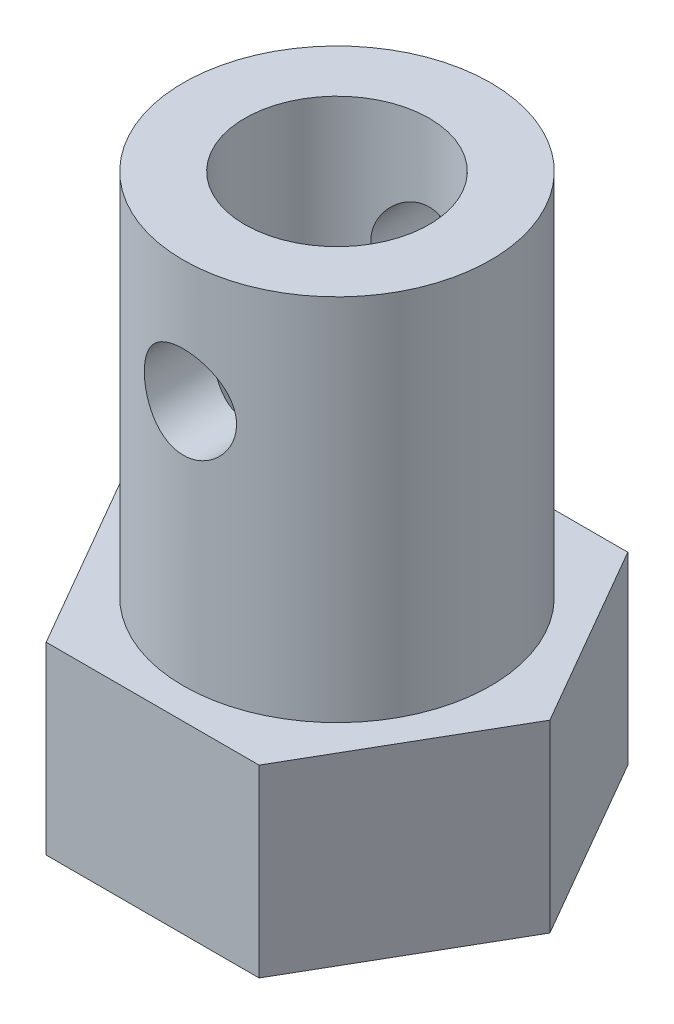
SolidWorks part; units mm, degrees
material "Brass"
ref_plane "Front Plane" through (0, 0, 0) normal (0, 0, 1) x (1, 0, 0)
ref_plane "Top Plane" through (0, 0, 0) normal (0, 1, 0) x (1, 0, 0)
ref_plane "Right Plane" through (0, 0, 0) normal (1, 0, 0) x (0, 0, -1)
sketch "Sketch1" plane through (0, 0, 0) normal (0, 1, 0) x (1, 0, 0)
  line L1 (6.9282, 0) -> (3.4641, 6)
  line L2 (3.4641, 6) -> (-3.4641, 6)
  line L3 (-3.4641, 6) -> (-6.9282, 0)
  line L4 (-6.9282, 0) -> (-3.4641, -6)
  line L5 (-3.4641, -6) -> (3.4641, -6)
  line L6 (3.4641, -6) -> (6.9282, 0)
  circle A0 centre (0, 0) radius 6 construction
  dimension "D1" = 12
extrude "Boss-Extrude1" add sketch "Sketch1" along normal blind 6
sketch "Sketch3" plane through (0, 6, 0) normal (0, 1, 0) x (1, 0, 0)
  circle A0 centre (0, 0) radius 5
  dimension "D1" = 10
extrude "Boss-Extrude2" add sketch "Sketch3" along normal blind 12
sketch "Sketch4" plane through (0, 18, 0) normal (0, 1, 0) x (1, 0, 0)
  circle A0 centre (0, 0) radius 3
  dimension "D1" = 6
extrude "Cut-Extrude1" cut sketch "Sketch4" against normal blind 14.4
sketch "Sketch5" plane through (0, 0, 0) normal (0, 0, 1) x (1, 0, 0)
  circle A0 centre (0, 14) radius 1.5
  dimension "D1" = 3
  dimension "D2" = 14
extrude "Cut-Extrude2" cut sketch "Sketch5" against normal through all both and the other way through all
sketch "Sketch6" plane through (0, 0, 0) normal (0, -1, 0) x (1, 0, 0)
  circle A0 centre (0, 0) radius 1.5
  dimension "D1" = 3
extrude "Cut-Extrude3" cut sketch "Sketch6" against normal blind 14.4
